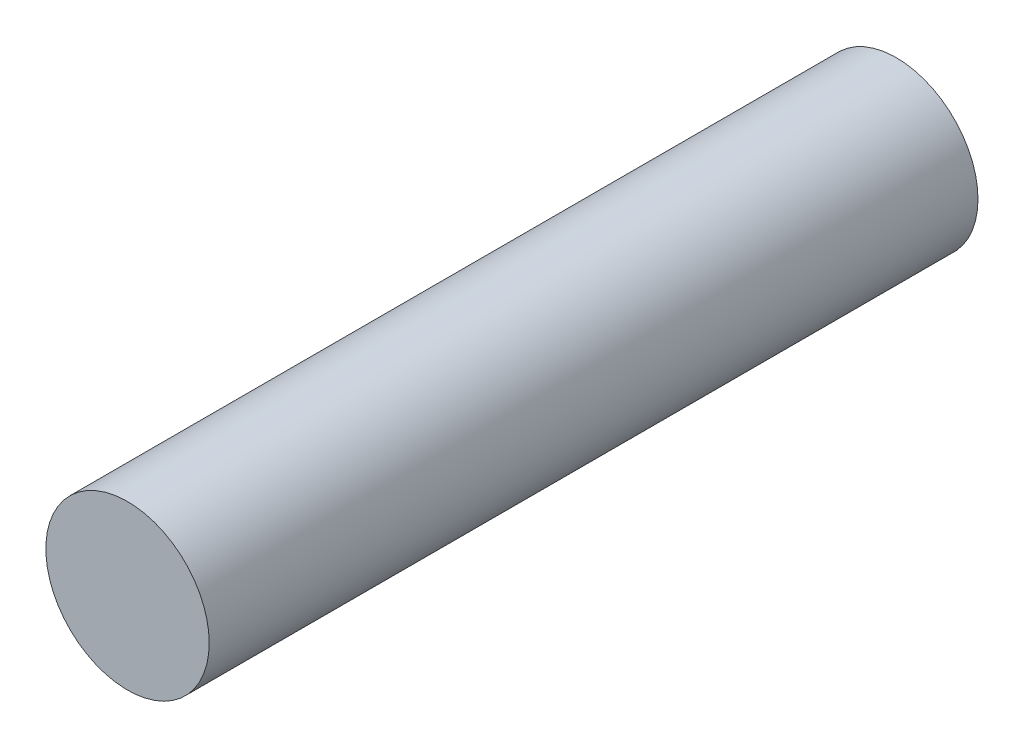
SolidWorks part; units mm, degrees
ref_plane "Front Plane" through (0, 0, 0) normal (0, 0, 1) x (1, 0, 0)
ref_plane "Top Plane" through (0, 0, 0) normal (0, 1, 0) x (1, 0, 0)
ref_plane "Right Plane" through (0, 0, 0) normal (1, 0, 0) x (0, 0, -1)
sketch "Sketch2" plane through (0, 0, 0) normal (0, 0, 1) x (1, 0, 0)
  circle A0 centre (0, 0) radius 0.85
  dimension "D1" = 1.7
extrude "Boss-Extrude1" add sketch "Sketch2" along normal blind 8
